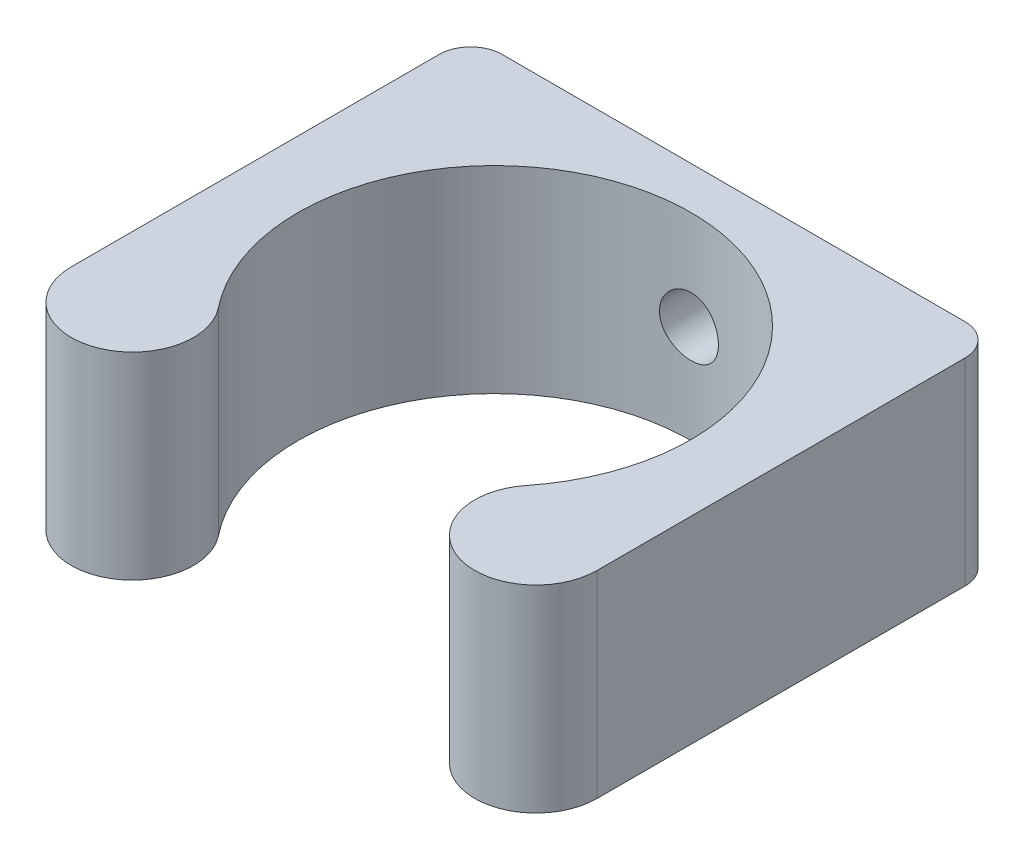
SolidWorks part; units mm, degrees
material "Chrome Stainless Steel"
ref_plane "Front Plane" through (0, 0, 0) normal (0, 0, 1) x (1, 0, 0)
ref_plane "Top Plane" through (0, 0, 0) normal (0, 1, 0) x (1, 0, 0)
ref_plane "Right Plane" through (0, 0, 0) normal (1, 0, 0) x (0, 0, -1)
sketch "Sketch2" plane through (0, 0, 0) normal (0, 1, 0) x (1, 0, 0)
  line L0 (-43.8561, 7.2408) -> (-43.8561, 39.4988)
  line L1 (-43.8561, 39.4988) -> (-1.3873, 39.4988)
  line L2 (-22.6217, 39.4988) -> (-22.6217, 36.0698)
  line L3 (-1.3873, 7.2408) -> (-1.3873, 39.4988)
  arc A0 (-43.8561, 7.2408) -> (-35.0481, 10.3155) centre (-38.9155, 7.2408) ccw
  arc A1 (-10.1954, 10.3155) -> (-35.0481, 10.3155) centre (-22.6217, 20.1948) ccw
  arc A2 (-1.3873, 7.2408) -> (-10.1954, 10.3155) centre (-6.328, 7.2408) cw
  dimension "D2" = 15.875
  dimension "D3" = 21.2344
  dimension "D4" = 32.258
extrude "Boss-Extrude1" add sketch "Sketch2" along normal blind 15.9512 contours A1 L2 L1 L0 A0 | A2 L3 L1 L2 A1
fillet "Fillet1" radius 2.54 2 edges at (-43.8561, 7.9756, -39.4988) (-1.3873, 7.9756, -39.4988)
sketch "Sketch3" plane through (0, 0, -39.4988) normal (0, 0, -1) x (-1, 0, 0)
  line L0 (41.3161, 15.9512) -> (3.9273, 15.9512) construction
  line L1 (3.9273, 15.9512) -> (3.9273, 0) construction
  circle A0 centre (22.6217, 7.9756) radius 2.3813
  point P4 (22.6217, 15.9512)
  point P7 (3.9273, 7.9756)
  dimension "D1" = 4.7625
extrude "Cut-Extrude1" cut sketch "Sketch3" against normal through all
